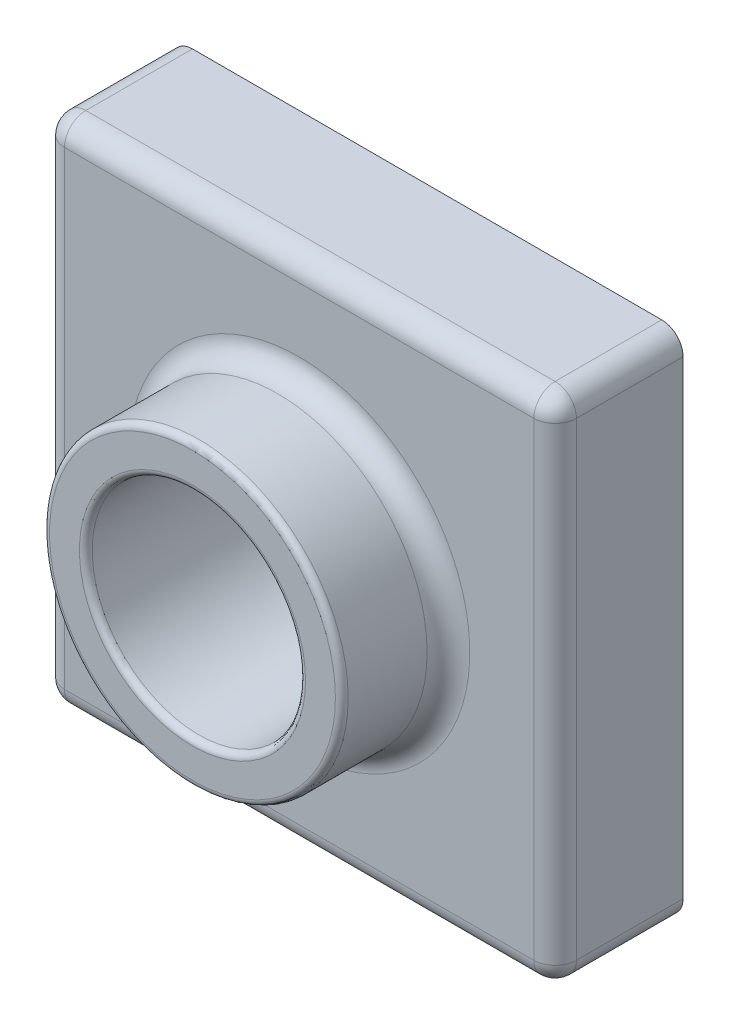
SolidWorks part; units mm, degrees
ref_plane "Front" through (0, 0, 0) normal (0, 0, 1) x (1, 0, 0)
ref_plane "Top" through (0, 0, 0) normal (0, 1, 0) x (1, 0, 0)
ref_plane "Right" through (0, 0, 0) normal (1, 0, 0) x (0, 0, -1)
sketch "Sketch1" plane through (0, 0, 0) normal (0, 0, 1) x (1, 0, 0)
  line L1 (-60, -60) -> (60, -60)
  line L2 (-60, -60) -> (-60, 60)
  line L3 (-60, 60) -> (60, 60)
  line L4 (60, -60) -> (60, 60)
  line L5 (-60, -60) -> (60, 60) construction
  line L6 (-60, 60) -> (60, -60) construction
  point P0 (0, 0)
  dimension "D1" = 120
  dimension "D2" = 120
extrude "Boss-Extrude1" add sketch "Sketch1" along normal blind 30
sketch "Sketch2" plane through (0, 0, 30) normal (0, 0, 1) x (1, 0, 0)
  circle A0 centre (0, 0) radius 35
  dimension "D1" = 70
extrude "Boss-Extrude2" add sketch "Sketch2" along normal blind 25
sketch "Sketch3" plane through (0, 0, 55) normal (0, 0, 1) x (1, 0, 0)
  circle A0 centre (0, 0) radius 25
  circle A1 centre (0, 0) radius 35 construction
  dimension "D1" = 10
extrude "Cut-Extrude3" cut sketch "Sketch3" against normal through all
fillet "Fillet1" radius 5 9 edges at (35, 0, 30) (-60, -60, 15) (60, -60, 15) (0, -60, 30) (60, 0, 30) (60, 60, 15) (-60, 60, 15) (0, 60, 30) (-60, 0, 30)
fillet "Fillet2" radius 1.5 2 edges at (35, 0, 55) (25, 0, 55)
shell "Shell1" thickness 2
